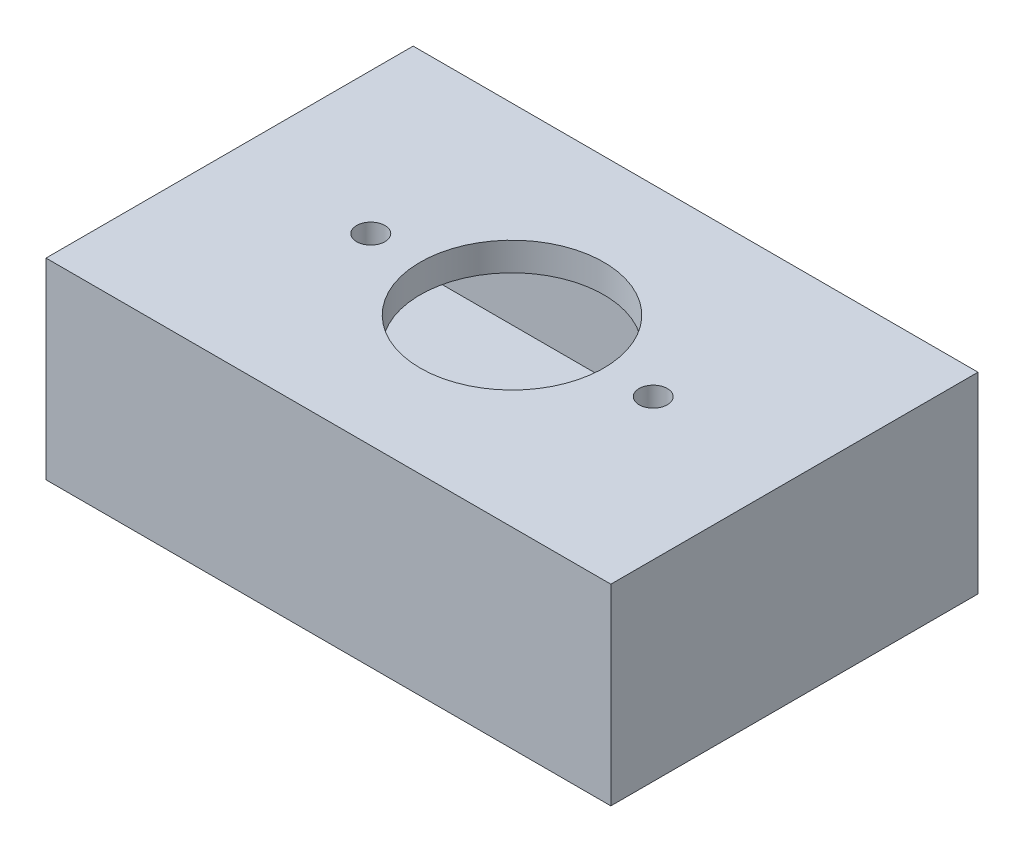
SolidWorks part; units mm, degrees
ref_plane "Front Plane" through (0, 0, 0) normal (0, 0, 1) x (1, 0, 0)
ref_plane "Top Plane" through (0, 0, 0) normal (0, 1, 0) x (1, 0, 0)
ref_plane "Right Plane" through (0, 0, 0) normal (1, 0, 0) x (0, 0, -1)
sketch "Sketch1" plane through (0, 0, 0) normal (0, 1, 0) x (1, 0, 0)
  line L1 (-100, 65) -> (100, 65)
  line L2 (-100, 65) -> (-100, -65)
  line L3 (-100, -65) -> (100, -65)
  line L4 (100, 65) -> (100, -65)
  line L5 (-100, 65) -> (100, -65) construction
  line L6 (-100, -65) -> (100, 65) construction
  point P0 (0, 0)
  dimension "D1" = 130
  dimension "D2" = 200
extrude "Boss-Extrude1" add sketch "Sketch1" along normal blind 58
shell "Shell1" thickness 10
sketch "Sketch2" plane through (0, 10, 0) normal (0, 1, 0) x (1, 0, 0)
  line L0 (0, -77.8873) -> (0, 72.769) construction
  line L1 (-134.4112, 0) -> (134.4112, 0) construction
  circle A0 centre (-15.5, 15.5) radius 1.5
  circle A1 centre (15.5, 15.5) radius 1.5
  circle A2 centre (-15.5, -15.5) radius 1.5
  circle A3 centre (15.5, -15.5) radius 1.5
  dimension "D1" = 3
  dimension "D2" = 28
  dimension "D3" = 28
extrude "Cut-Extrude1" cut sketch "Sketch2" against normal through all
sketch "Sketch3" plane through (0, 58, 0) normal (0, 1, 0) x (1, 0, 0)
  line L0 (100, -65) -> (100, 65) construction
  line L1 (100, -65) -> (100, 65)
  line L2 (-100, -65) -> (100, -65) construction
  line L3 (-100, 65) -> (-100, -65) construction
  line L4 (100, 65) -> (-100, 65) construction
  line L5 (-100, -65) -> (100, -65)
  line L6 (-100, 65) -> (-100, -65)
  line L7 (100, 65) -> (-100, 65)
extrude "Boss-Extrude2" add sketch "Sketch3" along normal blind 10
sketch "Sketch4" plane through (0, 68, 0) normal (0, 1, 0) x (1, 0, 0)
  line L0 (0, 0) -> (-50, 0)
  line L1 (-50, 0) -> (0, 0)
  line L2 (0, 0) -> (50, 0)
  circle A0 centre (0, 0) radius 32.5
  circle A1 centre (-50, 0) radius 5
  circle A2 centre (50, 0) radius 5
  dimension "D1" = 65
  dimension "D3" = 10
  dimension "D2" = 50
extrude "Cut-Extrude2" cut sketch "Sketch4" against normal up to next
